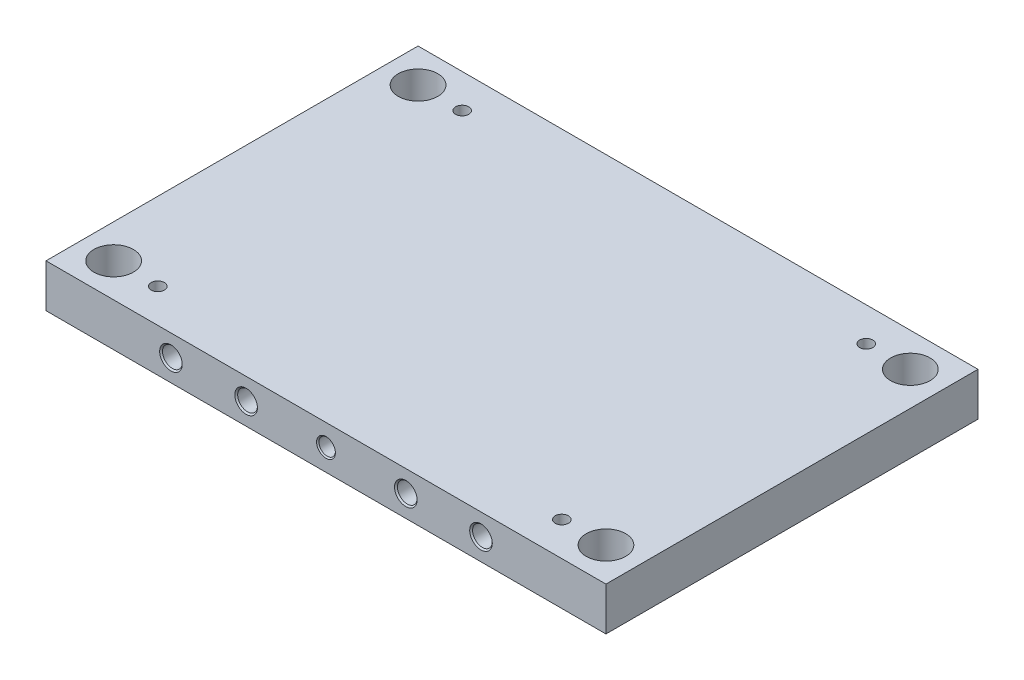
SolidWorks part; units mm, degrees
material "1.2312 (40CrMnMoS8-6)"
ref_plane "Płaszczyzna przednia" through (0, 0, 0) normal (0, 0, 1) x (1, 0, 0)
ref_plane "Płaszczyzna górna" through (0, 0, 0) normal (0, 1, 0) x (1, 0, 0)
ref_plane "Płaszczyzna prawa" through (0, 0, 0) normal (1, 0, 0) x (0, 0, -1)
sketch "Szkic1" plane through (0, 0, 0) normal (0, 1, 0) x (1, 0, 0)
  line L0 (298, 396) -> (298, 0) construction
  line L1 (0, 0) -> (596, 0)
  line L2 (0, 0) -> (0, 396)
  line L3 (0, 396) -> (596, 396)
  line L4 (596, 0) -> (596, 396)
  line L5 (0, 198) -> (596, 198) construction
  circle A0 centre (36, 360) radius 21
  circle A1 centre (36, 360) radius 24
  circle A2 centre (560, 360) radius 24
  circle A3 centre (560, 360) radius 21
  circle A4 centre (560, 36) radius 21
  circle A5 centre (560, 36) radius 24
  circle A6 centre (36, 36) radius 24
  circle A7 centre (36, 36) radius 21
  dimension "D3" = 48
  dimension "D4" = 42
  dimension "D1" = 396
  dimension "D2" = 596
  dimension "D5" = 524
  dimension "D6" = 324
extrude "Dodanie-wyciągnięcie1" add sketch "Szkic1" against normal blind 46 contours A6 A7 | L1 L4 L3 L2 A2 A1 A5 A6 | A5 A4 | A2 A3 | A1 A0
sketch "Szkic3" plane through (0, 0, 0) normal (0, 1, 0) x (1, 0, 0)
  line L0 (0, 0) -> (596, 0) construction
  line L1 (83, 360) -> (513, 360)
  line L2 (83, 360) -> (83, 36)
  line L3 (83, 36) -> (513, 36)
  line L4 (513, 360) -> (513, 36)
  line L6 (298, 396) -> (298, 0) construction
  line L7 (0, 396) -> (596, 396) construction
  dimension "D4" = 215
  dimension "D1" = 430
  dimension "D2" = 324
  dimension "D3" = 36
hole_wizard "Otwór gwintowany M161" positions "Szkic 3D1" profile "Szkic2" tap size "M16" standard "ISO" end condition through all
sketch3d "Szkic 3D1"
  point P0 (83, 0, -360)
  point P2 (513, 0, -360)
  point P4 (83, 0, -36)
  point P6 (513, 0, -36)
cosmetic thread "Gwint otworu1" parameters "D2"=16
cosmetic thread "Gwint otworu2" parameters "D2"=16
cosmetic thread "Gwint otworu3" parameters "D2"=16
cosmetic thread "Gwint otworu4" parameters "D2"=16
sketch "Szkic2" plane through (83, 0, -360) normal (1, 0, 0) x (0, 0, 1)
  line L0 (0, 0) -> (0, 46)
  line L1 (0, 46) -> (7, 46)
  line L2 (7, 46) -> (7, 0)
  line L5 (7, 0) -> (0, 0)
  line L11 (0, -6.35) -> (0, 107.95) construction
  dimension "Średnica otworu gwintowanego na wylot" = 14
  dimension "Głębokość otworu gwintowanego na wylot" = 46
sketch "Szkic5" plane through (0, 0, 0) normal (0, 0, 1) x (1, 0, 0)
  line L0 (298, 0) -> (298, -46) construction
  line L1 (0, 0) -> (596, 0) construction
  line L2 (0, -46) -> (596, -46) construction
  line L3 (213, 0) -> (213, -46) construction
  line L4 (133, 0) -> (133, -46) construction
  line L5 (133, -23) -> (213, -23) construction
  circle A0 centre (133, -23) radius 5
  circle A1 centre (213, -23) radius 5
  circle A2 centre (463, -23) radius 5
  circle A3 centre (383, -23) radius 5
  point P18 (298, -23)
  dimension "D3" = 10
  dimension "D4" = 10
  dimension "D1" = 85
  dimension "D2" = 165
extrude "Wytnij-wyciągnięcie1" cut sketch "Szkic5" against normal through all
hole_wizard "Otwór gwintowany M241" positions "Szkic 3D2" profile "Szkic6" tap size "M24" standard "ISO"
sketch3d "Szkic 3D2"
  point P0 (213, -23, 0)
  point P3 (133, -23, 0)
  point P6 (383, -23, 0)
  point P9 (463, -23, 0)
sketch "Szkic6" plane through (213, -23, 0) normal (1, 0, 0) x (0, -1, 0)
  line L0 (0, 0) -> (0, 41.309)
  line L1 (0, 41.309) -> (10.5, 35)
  line L2 (10.5, 35) -> (10.5, 1.525)
  line L3 (10.5, 1.525) -> (12.025, 0)
  line L5 (12.025, 0) -> (0, 0)
  line L6 (-10.5, 1.525) -> (-12.025, 0) construction
  line L10 (0, 41.309) -> (-10.5, 35) construction
  line L11 (0, -6.35) -> (0, 107.95) construction
  dimension "Średnica wiertła gwintu" = 21
  dimension "Głębokość otworu gwintowanego" = 35
  dimension "Średnica zewnętrznego pogłębienia stożkowego" = 24.05
  dimension "Kąt zewnętrznego pogłębienia stożkowego" = 90
  dimension "Kąt wiertła" = 118
cosmetic thread "Gwint otworu5" parameters "D1"=35, "D2"=24
cosmetic thread "Gwint otworu6" parameters "D1"=35, "D2"=24
cosmetic thread "Gwint otworu7" parameters "D1"=35, "D2"=24
cosmetic thread "Gwint otworu8" parameters "D1"=35, "D2"=24
ref_plane "Płaszczyzna1" through (0, 0, -198) normal (0, 0, 1) x (1, 0, 0)
mirror "Lustro1" about plane through (0, 0, -198) normal (0, 0, 1) of "Otwór gwintowany M241"
sketch "Szkic7" plane through (596, 0, 0) normal (1, 0, 0) x (0, 0, -1)
  line L0 (198, 0) -> (198, -46) construction
  line L1 (0, 0) -> (396, 0) construction
  line L2 (0, -46) -> (396, -46) construction
  point P6 (198, -23)
hole_wizard "Otwór gwintowany M201" positions "Szkic 3D3" profile "Szkic8" tap size "M20" standard "ISO"
sketch3d "Szkic 3D3"
  point P0 (298, -23, 0)
sketch "Szkic8" plane through (298, -23, 0) normal (1, 0, 0) x (0, -1, 0)
  line L0 (0, 0) -> (0, 57.7575)
  line L1 (0, 57.7575) -> (8.75, 52.5)
  line L2 (8.75, 52.5) -> (8.75, 1.275)
  line L3 (8.75, 1.275) -> (10.025, 0)
  line L5 (10.025, 0) -> (0, 0)
  line L6 (-8.75, 1.275) -> (-10.025, 0) construction
  line L10 (0, 57.7575) -> (-8.75, 52.5) construction
  line L11 (0, -6.35) -> (0, 107.95) construction
  dimension "Średnica wiertła gwintu" = 17.5
  dimension "Głębokość otworu gwintowanego" = 52.5
  dimension "Średnica zewnętrznego pogłębienia stożkowego" = 20.05
  dimension "Kąt zewnętrznego pogłębienia stożkowego" = 90
  dimension "Kąt wiertła" = 118
cosmetic thread "Gwint otworu9" parameters "D1"=40, "D2"=20
